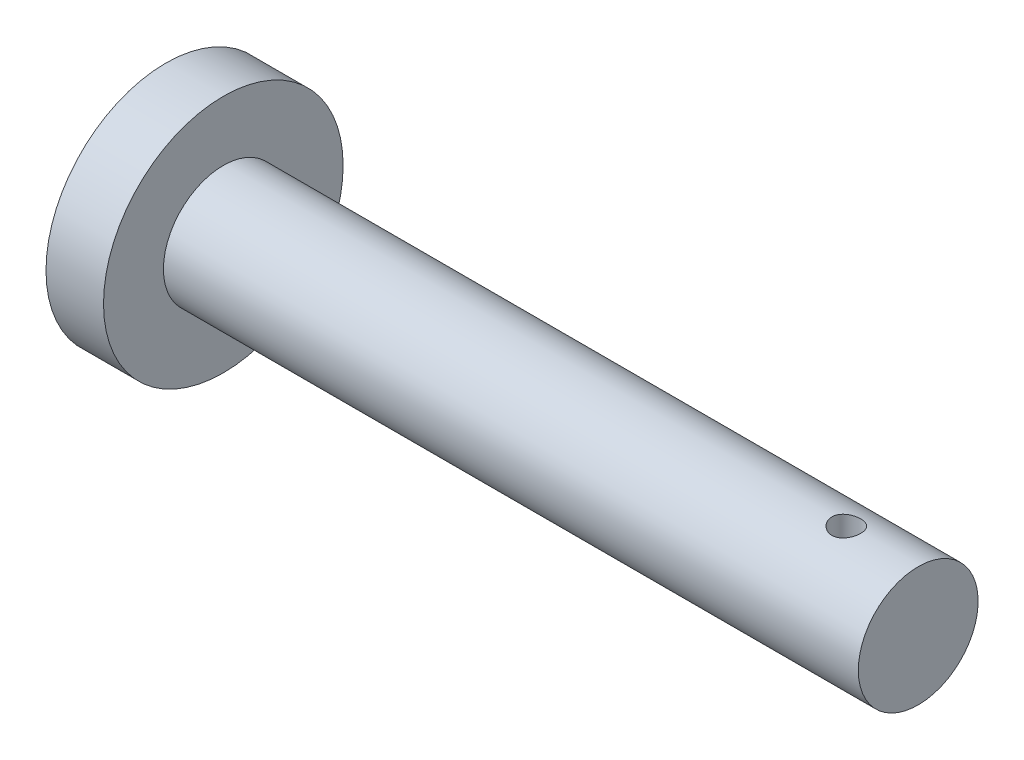
SolidWorks part; units mm, degrees
ref_plane "Front Plane" through (0, 0, 0) normal (0, 0, 1) x (1, 0, 0)
ref_plane "Top Plane" through (0, 0, 0) normal (0, 1, 0) x (1, 0, 0)
ref_plane "Right Plane" through (0, 0, 0) normal (1, 0, 0) x (0, 0, -1)
sketch "Sketch1" plane through (0, 0, 0) normal (0, 0, 1) x (1, 0, 0)
  line L0 (0, 0) -> (0, 12.5)
  line L1 (0, 12.5) -> (-145, 12.5)
  line L2 (-145, 12.5) -> (-145, 25)
  line L3 (-145, 25) -> (-157, 25)
  line L4 (-157, 25) -> (-157, 0)
  line L5 (-157, 0) -> (0, 0)
  dimension "D1" = 25
  dimension "D2" = 12.5
  dimension "D3" = 12
  dimension "D4" = 157
revolve "Revolve1" add sketch "Sketch1" angle 360 about L5
sketch "Sketch2" plane through (0, 0, 0) normal (0, 1, 0) x (1, 0, 0)
  line L0 (-145, -12.5) -> (-145, 12.5) construction
  circle A0 centre (-15, 0) radius 3
  dimension "D1" = 6
  dimension "D2" = 130
extrude "Cut-Extrude1" cut sketch "Sketch2" against normal through all both and the other way through all
